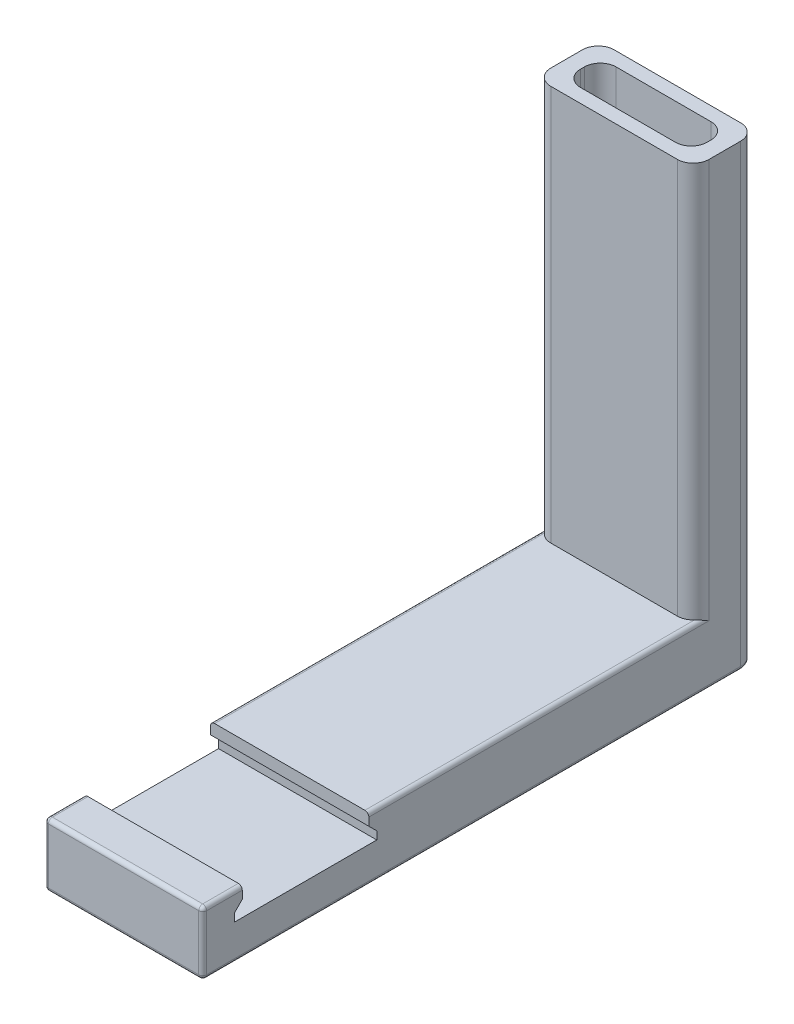
SolidWorks part; units mm, degrees
ref_plane "Front Plane" through (0, 0, 0) normal (0, 0, 1) x (1, 0, 0)
ref_plane "Top Plane" through (0, 0, 0) normal (0, 1, 0) x (1, 0, 0)
ref_plane "Right Plane" through (0, 0, 0) normal (1, 0, 0) x (0, 0, -1)
sketch "Sketch1" plane through (0, 0, 0) normal (0, 0, 1) x (1, 0, 0)
  line L1 (10, -4) -> (-10, -4)
  line L2 (10, -4) -> (10, 4)
  line L3 (10, 4) -> (-10, 4)
  line L4 (-10, -4) -> (-10, 4)
  line L5 (10, -4) -> (-10, 4) construction
  line L6 (10, 4) -> (-10, -4) construction
  point P0 (0, 0)
  dimension "D1" = 8
  dimension "D2" = 20
extrude "Boss-Extrude2" add sketch "Sketch1" along normal blind 70 contours L3 L4 L1 L2
sketch "Sketch3" plane through (0, 4, 0) normal (0, 1, 0) x (1, 0, 0)
  line L0 (10, -70) -> (10, 0) construction
  line L1 (-10, 0) -> (10, 0)
  line L2 (-10, 0) -> (-10, -8)
  line L3 (-10, -8) -> (10, -8)
  line L4 (10, 0) -> (10, -8)
  dimension "D1" = 8
extrude "Boss-Extrude3" add sketch "Sketch3" along normal blind 50
sketch "Sketch4" plane through (0, 54, 0) normal (0, 1, 0) x (1, 0, 0)
  line L0 (0, 0) -> (0, -4) construction
  line L1 (8, -6.25) -> (-8, -6.25)
  line L2 (8, -6.25) -> (8, -1.75)
  line L3 (8, -1.75) -> (-8, -1.75)
  line L4 (-8, -6.25) -> (-8, -1.75)
  line L5 (8, -6.25) -> (-8, -1.75) construction
  line L6 (8, -1.75) -> (-8, -6.25) construction
  line L7 (-10, -4) -> (0, -4) construction
  line L8 (-10, 0) -> (-10, -8) construction
  point P0 (0, -4)
  dimension "D1" = 16
  dimension "D2" = 4.5
extrude "Cut-Extrude2" cut sketch "Sketch4" against normal blind 40 contours L3 L4 L1 L2
fillet "Fillet1" radius 2 4 edges at (10, 25, 0) (10, 29, 8) (-10, 25, 0) (-10, 29, 8)
sketch "Sketch5" plane through (-10, 0, 0) normal (-1, 0, 0) x (0, 0, 1)
  line L0 (65, 4) -> (65, 2.5)
  line L1 (70, 4) -> (6, 4) construction
  line L2 (65, 2.5) -> (66, 1.5)
  line L8 (66, 1.5) -> (66, 0.5)
  line L9 (66, 0.5) -> (48, 0.5)
  line L10 (57, 4) -> (57, 0.5) construction
  line L11 (49, 4) -> (65, 4)
  line L12 (48, 1.5) -> (48, 0.5)
  line L13 (49, 2.5) -> (48, 1.5)
  line L14 (49, 4) -> (49, 2.5)
  dimension "D1" = 8
  dimension "D2" = 1.5
  dimension "D3" = 1
  dimension "D4" = 18
  dimension "D5" = 45
  dimension "D7" = 5
extrude "Cut-Extrude3" cut sketch "Sketch5" against normal blind 28
fillet "Fillet3" radius 0.5 13 edges at (10, -4, 36) (9.4142, -4, 0.5858) (0, -4, 0) (-9.4142, -4, 0.5858) (10, 4, 27.5) (0, 4, 70) (10, 0, 70) (-10, 0, 70) (-10, -4, 36) (-10, 4, 27.5) (0, -4, 70) (10, 4, 67.5) (-10, 4, 67.5)
fillet "Fillet4" radius 2 4 edges at (-8, 34, 6.25) (-8, 34, 1.75) (8, 34, 6.25) (8, 34, 1.75)
